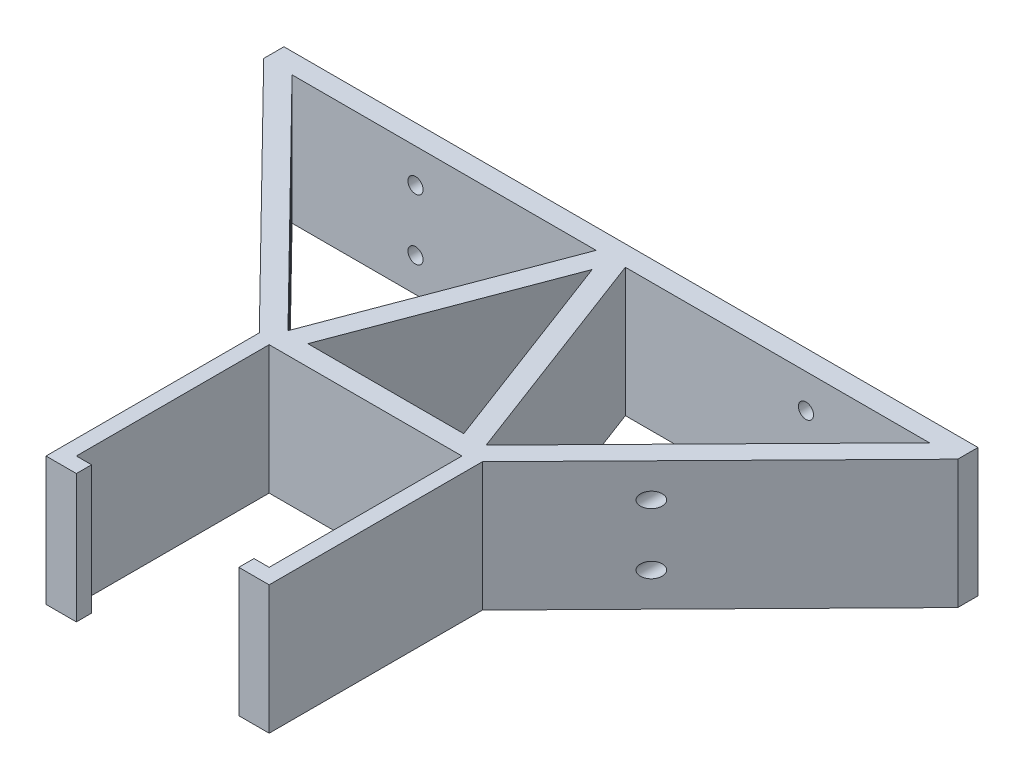
SolidWorks part; units mm, degrees
ref_plane "Front Plane" through (0, 0, 0) normal (0, 0, 1) x (1, 0, 0)
ref_plane "Top Plane" through (0, 0, 0) normal (0, 1, 0) x (1, 0, 0)
ref_plane "Right Plane" through (0, 0, 0) normal (1, 0, 0) x (0, 0, -1)
sketch "Sketch1" plane through (0, 0, 0) normal (0, 1, 0) x (1, 0, 0)
  line L0 (-21.1436, 1.371) -> (22.9564, 1.371) construction
  line L1 (-21.1436, -21.179) -> (22.9564, -21.179)
  line L2 (-21.1436, -21.179) -> (-21.1436, 23.921)
  line L3 (-21.1436, 23.921) -> (22.9564, 23.921)
  line L4 (22.9564, -21.179) -> (22.9564, 23.921)
  line L5 (-18.1436, 19.921) -> (19.9564, 19.921)
  line L6 (-18.1436, 19.921) -> (-18.1436, -18.179)
  line L7 (-18.1436, -18.179) -> (19.9564, -18.179)
  line L8 (19.9564, 19.921) -> (19.9564, -18.179)
  line L9 (0.9064, 23.921) -> (0.9064, -21.179) construction
  line L10 (0.9064, 1.371) -> (-66.2461, 69.7721) construction
  line L11 (-67.6733, 70.371) -> (69.4862, 70.371) construction
  line L12 (0.9064, 1.371) -> (22.9564, 23.921) construction
  line L13 (-18.1436, 19.921) -> (-14.0692, 23.921) construction
  line L14 (-14.0692, 23.921) -> (-21.1436, 16.9758) construction
  line L15 (19.9564, 19.921) -> (16.0295, 23.921) construction
  line L16 (16.0295, 23.921) -> (22.9564, 16.8652) construction
  line L21 (0.9064, 1.371) -> (0.9064, 70.371) construction
  line L22 (-19.1437, 18.9391) -> (-16.2893, 21.7414)
  line L23 (-19.1437, 18.9391) -> (-67.6733, 68.371)
  line L24 (-16.2893, 21.7414) -> (-64.8189, 71.1733)
  line L25 (-67.6733, 68.371) -> (-64.8189, 71.1733)
  line L26 (18.1022, 21.7414) -> (66.6318, 71.1733)
  line L27 (69.4862, 68.371) -> (66.6318, 71.1733)
  line L28 (20.9566, 18.9391) -> (69.4862, 68.371)
  line L29 (20.9566, 18.9391) -> (18.1022, 21.7414)
  line L30 (-67.6733, 68.371) -> (-67.6733, 72.371)
  line L31 (-67.6733, 68.371) -> (69.4862, 68.371)
  line L32 (-67.6733, 72.371) -> (69.4862, 72.371)
  line L33 (69.4862, 68.371) -> (69.4862, 72.371)
  line L34 (-18.1436, 19.921) -> (0.9064, 70.371) construction
  line L35 (-15.1436, -21.179) -> (16.9564, -21.179)
  line L36 (-15.1436, -21.179) -> (-15.1436, -18.179)
  line L37 (-15.1436, -18.179) -> (16.9564, -18.179)
  line L38 (16.9564, -21.179) -> (16.9564, -18.179)
  line L39 (0.9064, 70.371) -> (19.9564, 19.921) construction
  line L40 (-16.2083, 19.3844) -> (-19.9504, 20.7975)
  line L41 (-16.2083, 19.3844) -> (2.3847, 68.6242)
  line L42 (-19.9504, 20.7975) -> (-1.3574, 70.0372)
  line L43 (2.3847, 68.6242) -> (-1.3574, 70.0372)
  line L44 (21.7633, 20.7975) -> (3.1703, 70.0372)
  line L45 (-0.5718, 68.6242) -> (3.1703, 70.0372)
  line L46 (18.0212, 19.3844) -> (-0.5718, 68.6242)
  line L47 (18.0212, 19.3844) -> (21.7633, 20.7975)
  dimension "D3" = 3
  dimension "D4" = 3
  dimension "D5" = 4
  dimension "D6" = 3
  dimension "D7" = 4
  dimension "D10" = 4
  dimension "D11" = 44.45
  dimension "D12" = 0
  dimension "D13" = 6
  dimension "D14" = 6
  dimension "D15" = 4
  dimension "D16" = 2
  dimension "D2" = 38.1
  dimension "D17" = 38.1
  dimension "D8" = 2
extrude "Boss-Extrude1" add sketch "Sketch1" along normal blind 25.4 contours L1 L36 L7 L6 L22 L23 L2 | L38 L1 L4 L28 L29 L8 L7 | L5 L40 L22 | L40 L42 L3 L2 L23 L22 | L42 L40 L22 L24 L3 | L5 L41 L3 L24 L22 L40 | L42 L3 L24 | L3 L42 L24 L31 L23 L2 | L41 L46 L31 L42 L24 L3 | L5 L46 L3 L41 | L5 L47 L29 L26 L3 L46 | L29 L47 L44 L3 L26 | L47 L29 L28 L4 L3 L44 | L47 L5 L29 | L46 L3 L26 L44 L31 L41 | L44 L3 L4 L28 L31 L26 | L26 L31 L27 | L43 L45 L44 L31 L26 L27 L33 L32 L30 L25 L24 L42 | L46 L41 L31 | L31 L46 L45 L43 L42 | L46 L31 L41 L43 L45 | L45 L43 L41 L31 L44 | L25 L31 L24 | L3 L44 L26
sketch "Sketch2" plane through (0, 0, -72.371) normal (0, 0, -1) x (-1, 0, 0)
  line L0 (67.6733, 12.7) -> (-69.4862, 12.7) construction
  line L1 (67.6733, 25.4) -> (67.6733, 0) construction
  line L2 (-69.4862, 25.4) -> (-69.4862, 0) construction
  line L3 (-0.9064, 0) -> (-0.9064, 25.4) construction
  line L4 (67.6733, 0) -> (-69.4862, 0) construction
  line L5 (67.6733, 25.4) -> (-69.4862, 25.4) construction
  circle A0 centre (37.6733, 6.7) radius 1.5
  circle A1 centre (37.6733, 18.7) radius 1.5
  circle A2 centre (-39.4862, 18.7) radius 1.5
  circle A3 centre (-39.4862, 6.7) radius 1.5
  dimension "D1" = 3
  dimension "D2" = 6
  dimension "D3" = 30
extrude "Cut-Extrude1" cut sketch "Sketch2" against normal through all
equation "\"D10@Sketch1\"=\"D7@Sketch1\""
equation "\"D14@Sketch1\"=\"D13@Sketch1\""
equation "\"D8@Sketch1\"=\"D7@Sketch1\"/2"
